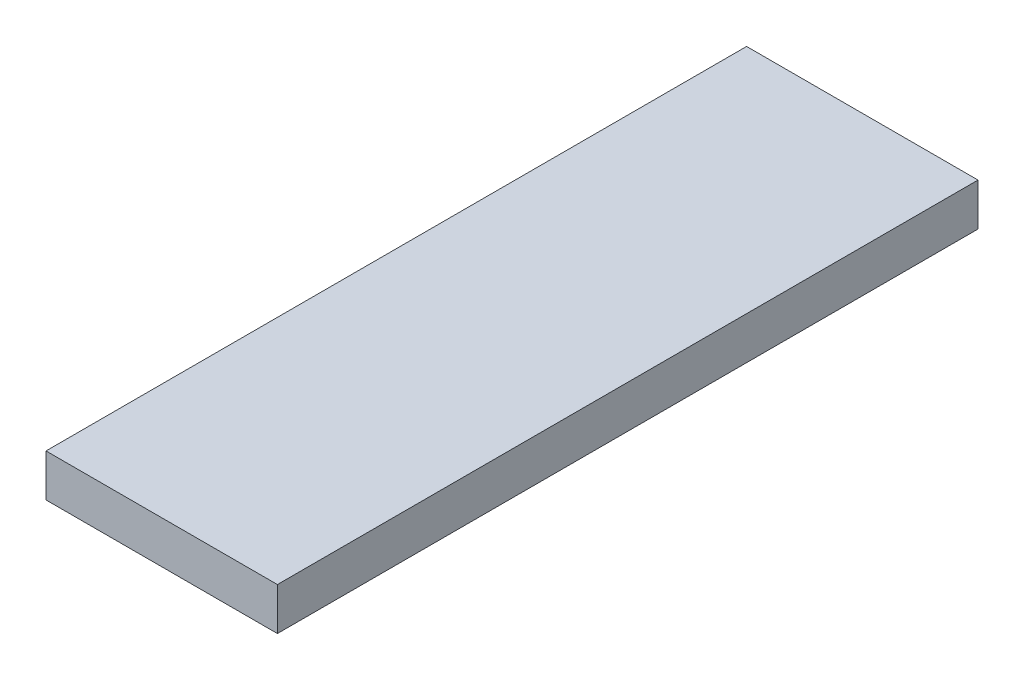
SolidWorks part; units mm, degrees
ref_plane "Front" through (0, 0, 0) normal (0, 0, 1) x (1, 0, 0)
ref_plane "Top" through (0, 0, 0) normal (0, 1, 0) x (1, 0, 0)
ref_plane "Right" through (0, 0, 0) normal (1, 0, 0) x (0, 0, -1)
sketch "Sketch1" plane through (0, 0, 0) normal (0, 1, 0) x (1, 0, 0)
  line L1 (0, 165) -> (54.5, 165)
  line L2 (0, 165) -> (0, 0)
  line L3 (0, 0) -> (54.5, 0)
  line L4 (54.5, 165) -> (54.5, 0)
  dimension "D1" = 165
  dimension "D2" = 54.5
extrude "Boss-Extrude1" add sketch "Sketch1" along normal blind 10
